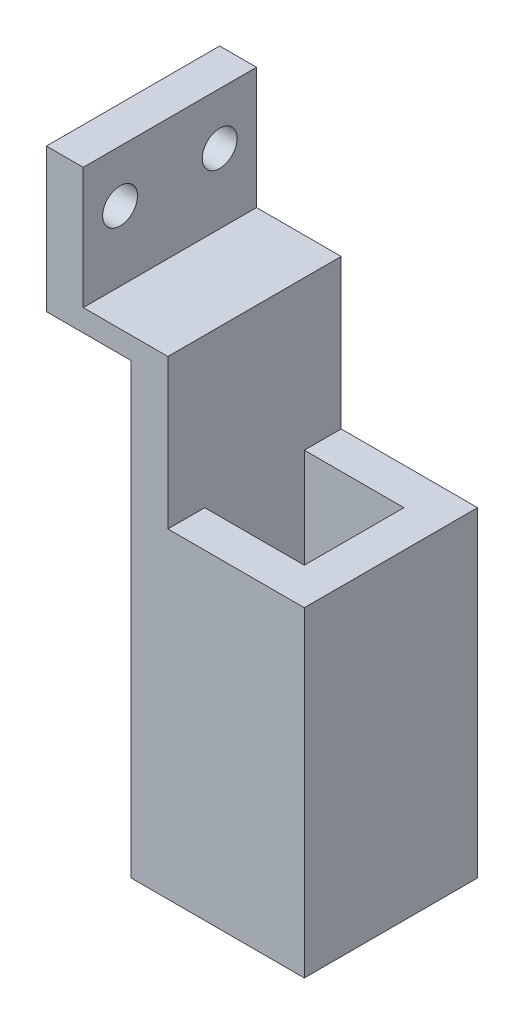
SolidWorks part; units mm, degrees
ref_plane "Front Plane" through (0, 0, 0) normal (0, 0, 1) x (1, 0, 0)
ref_plane "Top Plane" through (0, 0, 0) normal (0, 1, 0) x (1, 0, 0)
ref_plane "Right Plane" through (0, 0, 0) normal (1, 0, 0) x (0, 0, -1)
sketch "Sketch2" plane through (0, 0, 0) normal (0, 0, 1) x (1, 0, 0)
  line L0 (-12.2, 12.2) -> (-8.5, 12.2)
  line L1 (-8.5, 12.2) -> (-8.5, 0)
  line L2 (-8.5, 0) -> (0, 0)
  line L3 (0, 0) -> (0, -45)
  line L4 (0, -45) -> (10, -45)
  line L5 (10, -45) -> (10, -15)
  line L6 (10, -15) -> (13.7, -15)
  line L7 (13.7, -15) -> (13.7, -47.2)
  line L8 (13.7, -47.2) -> (-3.7, -47.2)
  line L9 (-3.7, -47.2) -> (-3.7, -2.2)
  line L10 (-3.7, -2.2) -> (-12.2, -2.2)
  line L11 (-12.2, -2.2) -> (-12.2, 12.2)
  dimension "D1" = 8.5
  dimension "D2" = 3.7
  dimension "D3" = 12.2
  dimension "D4" = 45
  dimension "D5" = 30
  dimension "D6" = 2.2
  dimension "D7" = 10
extrude "Boss-Extrude1" add sketch "Sketch2" along normal blind 17.4
sketch "Sketch3" plane through (0, -45, 0) normal (0, -1, 0) x (1, 0, 0)
  line L8 (0, 17.4) -> (10, 17.4)
  line L9 (0, 17.4) -> (0, 13.7)
  line L10 (10, 17.4) -> (10, 13.7)
  line L11 (0, 13.7) -> (10, 13.7)
  line L12 (0, 0) -> (10, 0)
  line L13 (0, 0) -> (0, 3.7)
  line L14 (10, 0) -> (10, 3.7)
  line L15 (0, 3.7) -> (10, 3.7)
  dimension "D1" = 3.7
extrude "Boss-Extrude3" add sketch "Sketch3" against normal blind 30
sketch "Sketch4" plane through (-8.5, 0, 0) normal (1, 0, 0) x (0, 0, -1)
  line L2 (-17.4, 0) -> (0, 0) construction
  line L3 (-13.7, 7) -> (-3.7, 7) construction
  line L4 (0, 0) -> (0, 12.2) construction
  circle A0 centre (-13.7, 7) radius 1.75
  circle A1 centre (-3.7, 7) radius 1.75
  point P4 (-8.7, 7)
  dimension "D2" = 3.5
  dimension "D1" = 10
  dimension "D3" = 8.7
  dimension "D4" = 7
extrude "Cut-Extrude1" cut sketch "Sketch4" against normal through all
